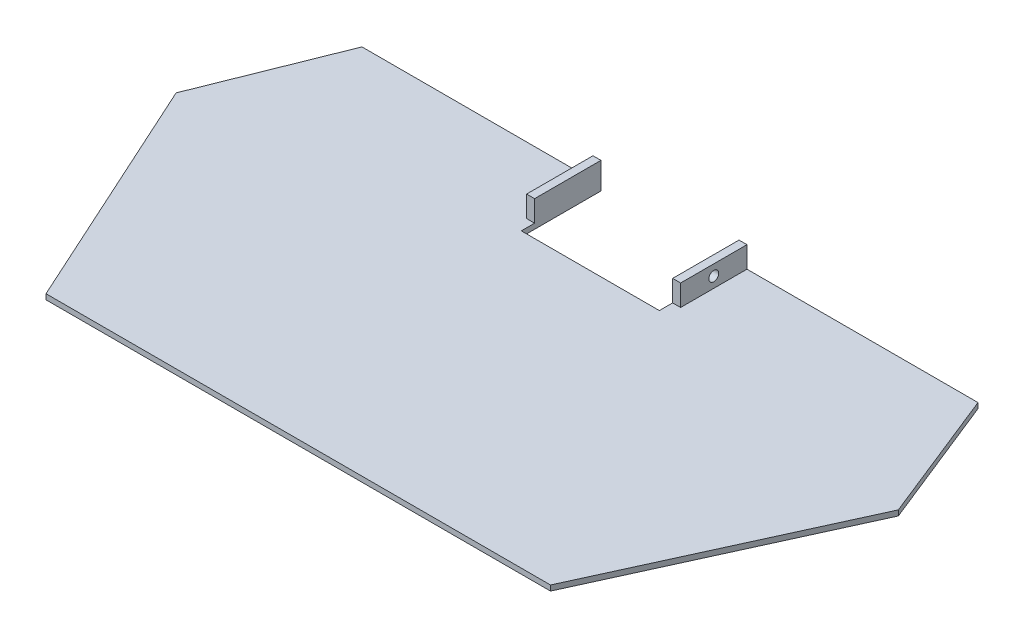
SolidWorks part; units mm, degrees
ref_plane "前视基准面" through (0, 0, 0) normal (0, 0, 1) x (1, 0, 0)
ref_plane "上视基准面" through (0, 0, 0) normal (0, 1, 0) x (1, 0, 0)
ref_plane "右视基准面" through (0, 0, 0) normal (1, 0, 0) x (0, 0, -1)
other "Configuration Table"
sketch "草图1" plane through (0, 0, 0) normal (0, 1, 0) x (1, 0, 0)
  line L0 (0, 57.6481) -> (0, -101.8228) construction
  line L1 (26, 30) -> (-26, 30)
  line L2 (-26, 30) -> (-26, 60)
  line L3 (-26, 60) -> (-116, 60)
  line L4 (-116, 60) -> (-136, 10)
  line L5 (-136, 10) -> (-95, -80)
  line L6 (-95, -80) -> (95, -80)
  line L7 (136, 10) -> (95, -80)
  line L8 (116, 60) -> (136, 10)
  line L9 (26, 60) -> (116, 60)
  line L10 (26, 30) -> (26, 60)
  point P12 (0, -80)
  point P13 (0, 30)
  dimension "D1" = 26
  dimension "D2" = 90
  dimension "D3" = 140
  dimension "D4" = 50
  dimension "D5" = 30
  dimension "D6" = 30
  dimension "D7" = 190
  dimension "D8" = 20
extrude "凸台-拉伸1" add sketch "草图1" along normal blind 2
sketch "草图2" plane through (0, 2, 0) normal (0, 1, 0) x (1, 0, 0)
  line L0 (0, 53.9156) -> (0, 0) construction
  line L1 (29, 60) -> (29, 35)
  line L2 (-26, 60) -> (-29, 60)
  line L3 (-26, 60) -> (-26, 35)
  line L4 (-26, 35) -> (-29, 35)
  line L5 (-29, 60) -> (-29, 35)
  line L6 (26, 35) -> (29, 35)
  line L7 (26, 60) -> (26, 35)
  line L8 (26, 60) -> (29, 60)
  dimension "D1" = 3
  dimension "D2" = 25
extrude "凸台-拉伸2" add sketch "草图2" along normal blind 8
sketch "草图3" plane through (26, 0, 0) normal (-1, 0, 0) x (0, 0, 1)
  line L0 (-47.5, 10) -> (-47.5, 2.577) construction
  line L1 (-60, 10) -> (-35, 10) construction
  circle A0 centre (-47.5, 6) radius 1.85
  dimension "D1" = 3.7
  dimension "D2" = 4
extrude "切除-拉伸1" cut sketch "草图3" against normal blind 8
